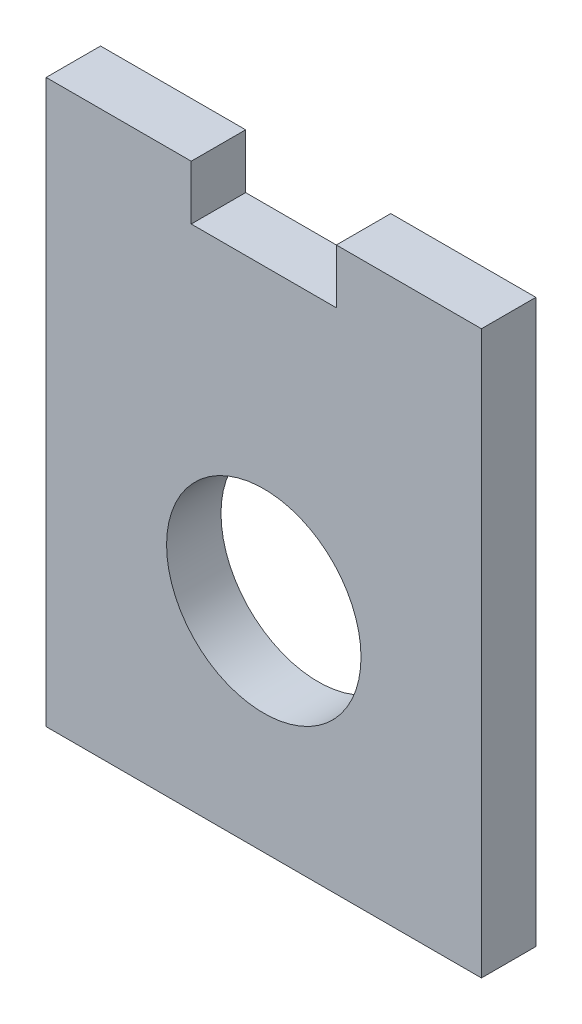
SolidWorks part; units mm, degrees
ref_plane "Front Plane" through (0, 0, 0) normal (0, 0, 1) x (1, 0, 0)
ref_plane "Top Plane" through (0, 0, 0) normal (0, 1, 0) x (1, 0, 0)
ref_plane "Right Plane" through (0, 0, 0) normal (1, 0, 0) x (0, 0, -1)
sketch "Sketch1" plane through (0, 0, 0) normal (0, 0, 1) x (1, 0, 0)
  line L0 (0, 0) -> (0, 49.2125)
  line L1 (0, 49.2125) -> (12.7, 49.2125)
  line L2 (12.7, 49.2125) -> (12.7, 44.45)
  line L3 (12.7, 44.45) -> (25.4, 44.45)
  line L4 (25.4, 44.45) -> (25.4, 49.2125)
  line L5 (25.4, 49.2125) -> (38.1, 49.2125)
  line L6 (38.1, 49.2125) -> (38.1, 0)
  line L7 (38.1, 0) -> (0, 0)
  line L8 (19.05, 19.05) -> (19.05, 0) construction
  circle A0 centre (19.05, 19.05) radius 8.509
  dimension "D6" = 17.018
  dimension "D1" = 19.05
  dimension "D2" = 44.45
  dimension "D3" = 4.7625
  dimension "D4" = 38.1
  dimension "D5" = 12.7
extrude "Boss-Extrude1" add sketch "Sketch1" along normal blind 4.7625
